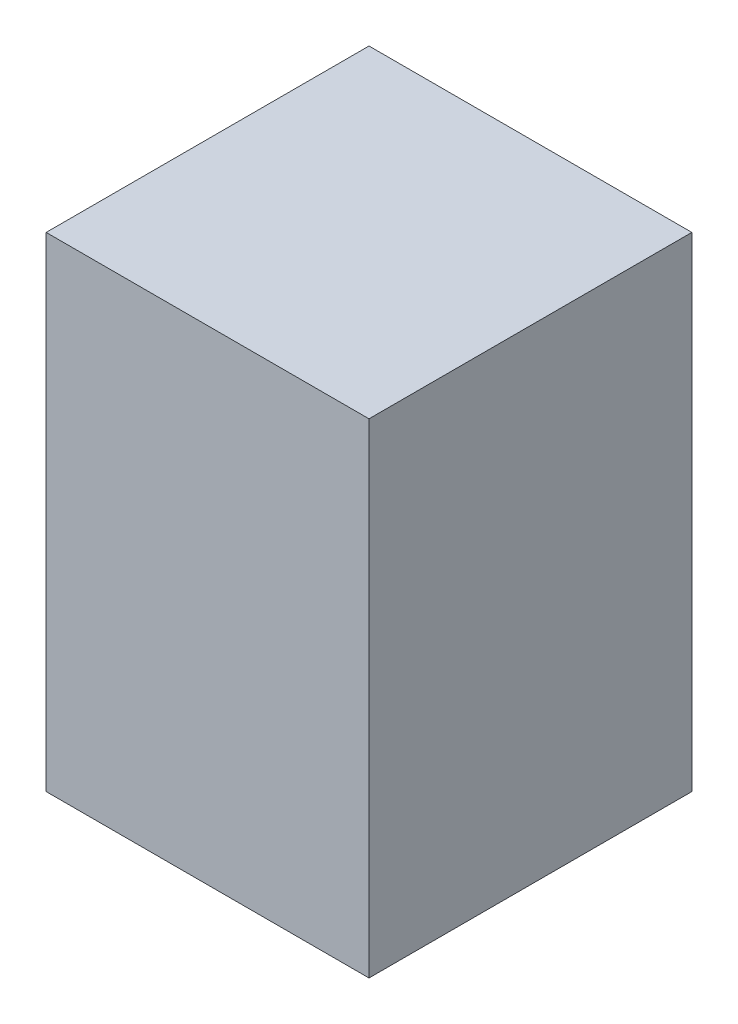
SolidWorks part; units mm, degrees
ref_plane "Front Plane" through (0, 0, 0) normal (0, 0, 1) x (1, 0, 0)
ref_plane "Top Plane" through (0, 0, 0) normal (0, 1, 0) x (1, 0, 0)
ref_plane "Right Plane" through (0, 0, 0) normal (1, 0, 0) x (0, 0, -1)
other "Configuration Table"
sketch "Sketch1" plane through (0, 0, 0) normal (0, 0, 1) x (1, 0, 0)
  line L1 (1260, 0) -> (1340, 0)
  line L2 (1260, 0) -> (1260, 120)
  line L3 (1260, 120) -> (1340, 120)
  line L4 (1340, 0) -> (1340, 120)
extrude "STORE_ayak_2_1" add sketch "Sketch1" against normal blind 80 from offset 40 separate body
